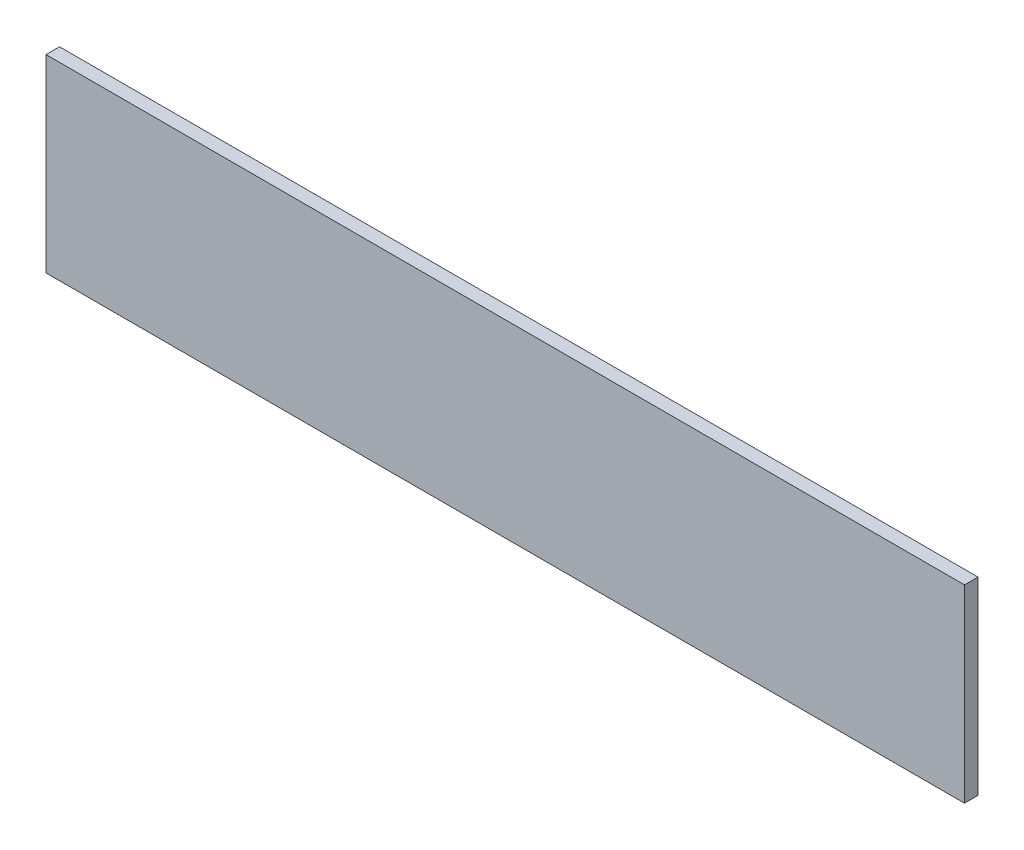
SolidWorks part; units mm, degrees
ref_plane "Front Plane" through (0, 0, 0) normal (0, 0, 1) x (1, 0, 0)
ref_plane "Top Plane" through (0, 0, 0) normal (0, 1, 0) x (1, 0, 0)
ref_plane "Right Plane" through (0, 0, 0) normal (1, 0, 0) x (0, 0, -1)
sketch "Sketch1" plane through (0, 0, 0) normal (0, 0, 1) x (1, 0, 0)
  line L1 (-431.8, -88.9) -> (431.8, -88.9)
  line L2 (-431.8, -88.9) -> (-431.8, 88.9)
  line L3 (-431.8, 88.9) -> (431.8, 88.9)
  line L4 (431.8, -88.9) -> (431.8, 88.9)
  line L5 (-431.8, -88.9) -> (431.8, 88.9) construction
  line L6 (-431.8, 88.9) -> (431.8, -88.9) construction
  point P0 (0, 0)
  dimension "D1" = 177.8
  dimension "D2" = 863.6
extrude "Boss-Extrude1" add sketch "Sketch1" along normal blind 12.7
sketch "Sketch2" plane through (0, 0, 0) normal (0, 0, 1) x (1, 0, 0)
  line L0 (-431.8, 0) -> (431.8, 0) construction
  line L1 (-431.8, 88.9) -> (-431.8, -88.9) construction
  line L2 (431.8, -88.9) -> (431.8, 88.9) construction
  line L3 (0, 88.9) -> (0, -88.9) construction
  line L4 (431.8, 88.9) -> (-431.8, 88.9) construction
  line L5 (-431.8, -88.9) -> (431.8, -88.9) construction
  circle A0 centre (-425.45, 0) radius 3.175
  circle A1 centre (425.45, 0) radius 3.175
  dimension "D1" = 6.35
  dimension "D2" = 6.35
extrude "Cut-Extrude3" cut sketch "Sketch2" along normal blind 11.43
sketch "Sketch3" plane through (0, 0, 0) normal (0, 0, -1) x (-1, 0, 0)
  line L0 (-425.45, 0) -> (-425.45, 88.9) construction
  line L1 (-431.8, 88.9) -> (431.8, 88.9) construction
  line L2 (-431.8, 0) -> (431.8, 0) construction
  line L3 (-431.8, -88.9) -> (-431.8, 88.9) construction
  line L4 (431.8, 88.9) -> (431.8, -88.9) construction
  line L5 (0, 88.9) -> (0, -88.9) construction
  line L6 (431.8, -88.9) -> (-431.8, -88.9) construction
  circle A0 centre (-425.45, 44.45) radius 2.5
  circle A1 centre (425.45, 44.45) radius 2.5
  circle A2 centre (425.45, -44.45) radius 2.5
  circle A3 centre (-425.45, -44.45) radius 2.5
  dimension "D1" = 5
extrude "Cut-Extrude4" cut sketch "Sketch3" against normal blind 8
sketch "Sketch5" plane through (0, 0, 0) normal (0, 0, -1) x (-1, 0, 0)
  line L0 (-431.8, -82.55) -> (431.8, -82.55) construction
  line L1 (-431.8, -88.9) -> (-431.8, 88.9) construction
  line L2 (431.8, 88.9) -> (431.8, -88.9) construction
  line L3 (431.8, -88.9) -> (-431.8, -88.9) construction
  circle A0 centre (-425.45, -82.55) radius 2.5
  circle A1 centre (-212.725, -82.55) radius 2.5
  circle A2 centre (0, -82.55) radius 2.5
  circle A3 centre (212.725, -82.55) radius 2.5
  circle A4 centre (425.45, -82.55) radius 2.5
  dimension "D3" = 5
  dimension "D1" = 6.35
  dimension "D2" = 6.35
  dimension "D4" = 5
extrude "Cut-Extrude6" cut sketch "Sketch5" against normal blind 8
sketch "Sketch6" plane through (0, 0, 0) normal (0, 0, -1) x (-1, 0, 0)
  line L0 (-425.45, -82.55) -> (-212.725, -82.55) construction
  circle A0 centre (-319.0875, -82.55) radius 3.175
  circle A1 centre (-106.3625, -82.55) radius 3.175
  circle A2 centre (106.3625, -82.55) radius 3.175
  circle A3 centre (319.0875, -82.55) radius 3.175
  dimension "D1" = 6.35
  dimension "D2" = 4
extrude "Cut-Extrude7" cut sketch "Sketch6" against normal blind 11.43
